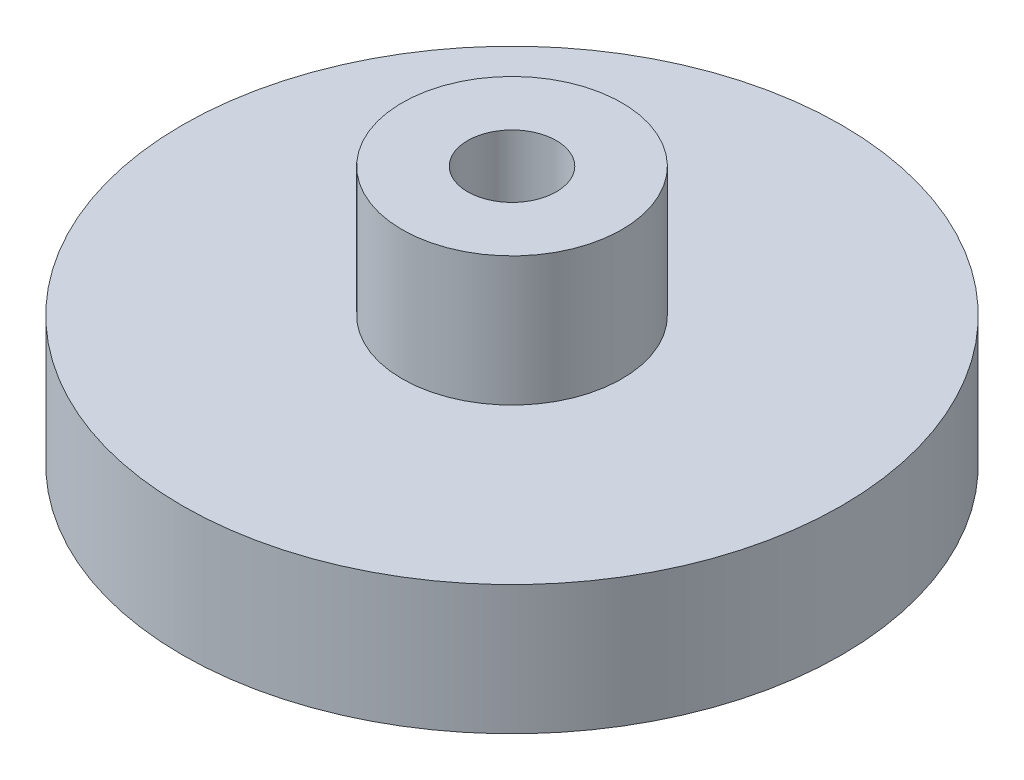
SolidWorks part; units mm, degrees
ref_plane "Front Plane" through (0, 0, 0) normal (0, 0, 1) x (1, 0, 0)
ref_plane "Top Plane" through (0, 0, 0) normal (0, 1, 0) x (1, 0, 0)
ref_plane "Right Plane" through (0, 0, 0) normal (1, 0, 0) x (0, 0, -1)
sketch "Sketch1" plane through (0, 0, 0) normal (0, 1, 0) x (1, 0, 0)
  circle A0 centre (0, 0) radius 14.85
  circle A1 centre (0, 0) radius 2
  dimension "D1" = 29.7
  dimension "D2" = 4
extrude "Boss-Extrude1" add sketch "Sketch1" along normal blind 5.82
sketch "Sketch2" plane through (0, 5.82, 0) normal (0, 1, 0) x (1, 0, 0)
  circle A0 centre (0, 0) radius 2
  circle A1 centre (0, 0) radius 2 construction
  circle A2 centre (0, 0) radius 4.95
  dimension "D1" = 9.9
extrude "Boss-Extrude2" add sketch "Sketch2" along normal blind 5.82
